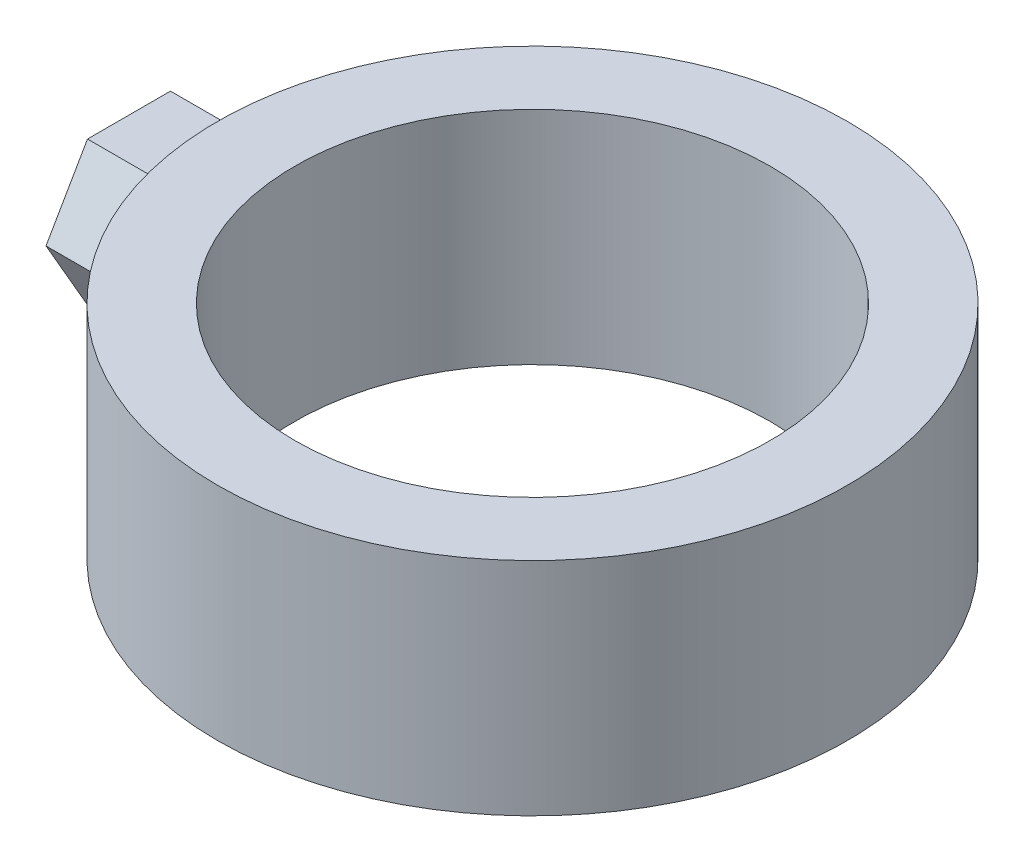
SolidWorks part; units mm, degrees
ref_plane "Спереди (XY)" through (0, 0, 0) normal (0, 0, 1) x (1, 0, 0)
ref_plane "Сверху (XZ)" through (0, 0, 0) normal (0, 1, 0) x (1, 0, 0)
ref_plane "Справа (ZY)" through (0, 0, 0) normal (1, 0, 0) x (0, 0, -1)
sketch "Эскиз2" plane through (0, 0, 0) normal (0, 1, 0) x (1, 0, 0)
  circle A0 centre (0, 0) radius 21.5
  circle A1 centre (0, 0) radius 28.5
  dimension "D1" = 43
  dimension "D2" = 7
extrude "Бобышка-Вытянуть1" add sketch "Эскиз2" along normal mid plane 20
sketch "Эскиз3" plane through (0, 0, 0) normal (1, 0, 0) x (0, 0, -1)
  line L1 (7.5056, 0) -> (3.7528, 6.5)
  line L2 (3.7528, 6.5) -> (-3.7528, 6.5)
  line L3 (-3.7528, 6.5) -> (-7.5056, 0)
  line L4 (-7.5056, 0) -> (-3.7528, -6.5)
  line L5 (-3.7528, -6.5) -> (3.7528, -6.5)
  line L6 (3.7528, -6.5) -> (7.5056, 0)
  circle A0 centre (0, 0) radius 6.5 construction
  dimension "D1" = 13
extrude "Бобышка-Вытянуть2" add sketch "Эскиз3" against normal blind 11.5 from offset 25 offset against normal yes
sketch "Эскиз4" plane through (-36.5, 0, 0) normal (-1, 0, 0) x (0, 0, 1)
  circle A0 centre (0, 0) radius 4
  dimension "D1" = 8
extrude "Вырез-Вытянуть2" cut sketch "Эскиз4" against normal blind 5
